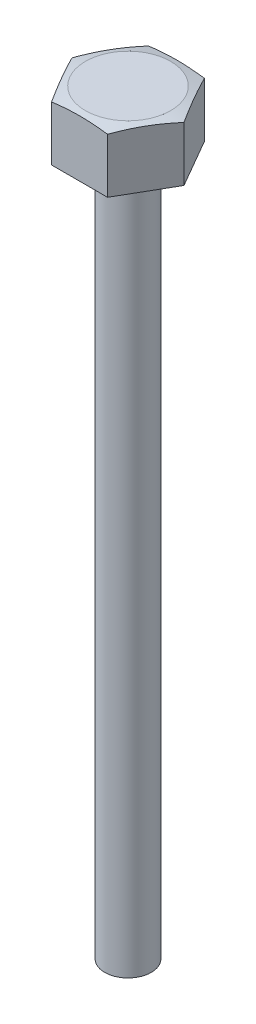
SolidWorks part; units mm, degrees
ref_plane "前视基准面" through (0, 0, 0) normal (0, 0, 1) x (1, 0, 0)
ref_plane "上视基准面" through (0, 0, 0) normal (0, 1, 0) x (1, 0, 0)
ref_plane "右视基准面" through (0, 0, 0) normal (1, 0, 0) x (0, 0, -1)
sketch "草图1" plane through (0, 0, 0) normal (0, 1, 0) x (1, 0, 0)
  line L1 (-7.2169, 12.5) -> (-14.4338, 0)
  line L2 (-14.4338, 0) -> (-7.2169, -12.5)
  line L3 (-7.2169, -12.5) -> (7.2169, -12.5)
  line L4 (7.2169, -12.5) -> (14.4338, 0)
  line L5 (14.4338, 0) -> (7.2169, 12.5)
  line L6 (7.2169, 12.5) -> (-7.2169, 12.5)
  circle A0 centre (0, 0) radius 12.5 construction
  point P1 (0, 0)
  point P10 (0, 0)
  point P11 (0, 12.5)
  dimension "D1" = 25
extrude "凸台-拉伸1" add sketch "草图1" against normal blind 15
sketch "草图2" plane through (0, -15, 0) normal (0, -1, 0) x (1, 0, 0)
  circle A0 centre (0, 0) radius 6
  dimension "D1" = 12
extrude "凸台-拉伸2" add sketch "草图2" along normal blind 180
sketch "草图7" plane through (0, 0, 0) normal (0, 1, 0) x (1, 0, 0)
  circle A0 centre (0, 0) radius 11
  dimension "D1" = 22
sketch "草图9" plane through (0, 0, 0) normal (0, 0, 1) x (1, 0, 0)
  line L0 (11, 0) -> (-11, 0) construction
  line L1 (11, 0) -> (-11, 0) construction
  line L2 (11, 0) -> (14.4338, -0.9201)
  line L3 (14.4338, -15) -> (14.4338, 0) construction
  line L4 (11, 0) -> (14.4338, 0)
  line L5 (14.4338, 0) -> (14.4338, -0.9201)
  dimension "D1" = 15
revolve "切除-旋转1" cut sketch "草图9" angle 360 about axis through (0, -195, 0) along (0, 1, 0)
